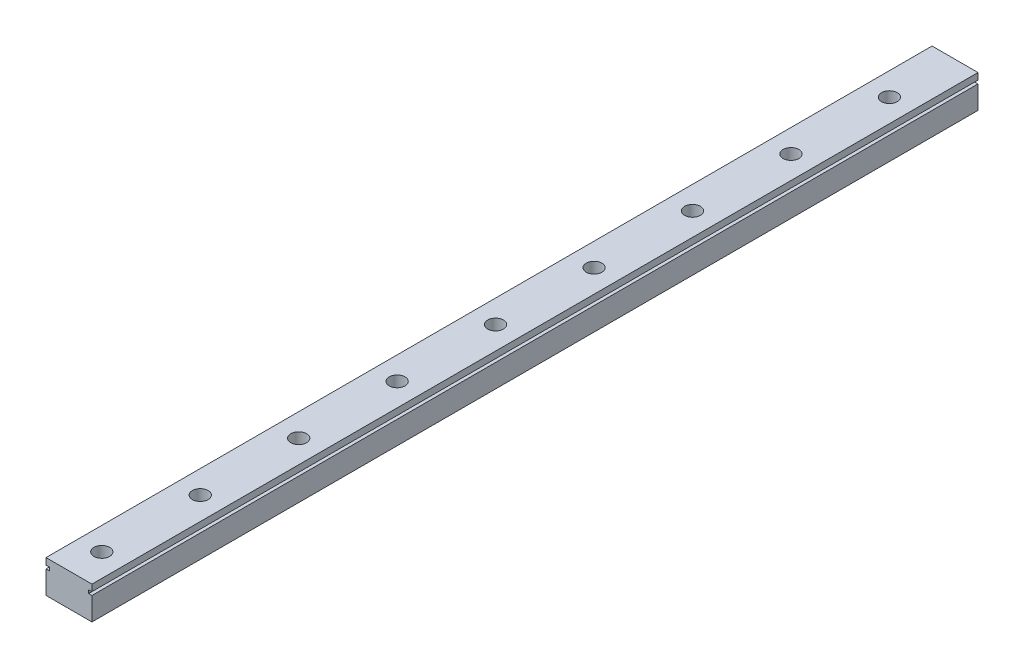
SolidWorks part; units mm, degrees
ref_plane "Front Plane" through (0, 0, 0) normal (0, 0, 1) x (1, 0, 0)
ref_plane "Top Plane" through (0, 0, 0) normal (0, 1, 0) x (1, 0, 0)
ref_plane "Right Plane" through (0, 0, 0) normal (1, 0, 0) x (0, 0, -1)
sketch "Sketch1" plane through (0, 0, 0) normal (0, 0, 1) x (1, 0, 0)
  line L0 (0, 4) -> (0, 5)
  line L1 (0, 0) -> (7, 0)
  line L2 (0, 0) -> (0, 3.5)
  line L3 (0, 5) -> (7, 5)
  line L4 (7, 0) -> (7, 3.5)
  line L5 (0, 4) -> (0.5, 4)
  line L6 (7, 4) -> (7, 5)
  line L7 (0, 3.5) -> (0.5, 3.5)
  line L8 (0.5, 4) -> (0.5, 3.5)
  line L9 (7, 4) -> (6.5, 4)
  line L11 (7, 3.5) -> (6.5, 3.5)
  line L12 (6.5, 4) -> (6.5, 3.5)
  dimension "D1" = 7
  dimension "D2" = 5
  dimension "D3" = 0.5
  dimension "D4" = 1
  dimension "D5" = 0.5
extrude "Boss-Extrude1" add sketch "Sketch1" along normal blind 135
sketch "Sketch2" plane through (0, 5, 0) normal (0, 1, 0) x (1, 0, 0)
  line L0 (3.5, 0) -> (3.5, -135) construction
  line L1 (7, 0) -> (0, 0) construction
  line L2 (7, -135) -> (0, -135) construction
  circle A0 centre (3.5, -130) radius 1.2
  circle A1 centre (3.5, -115) radius 1.2
  circle A2 centre (3.5, -100) radius 1.2
  circle A3 centre (3.5, -85) radius 1.2
  circle A4 centre (3.5, -70) radius 1.2
  circle A5 centre (3.5, -55) radius 1.2
  circle A6 centre (3.5, -40) radius 1.2
  circle A7 centre (3.5, -25) radius 1.2
  circle A8 centre (3.5, -10) radius 1.2
  circle A9 centre (3.5, 5) radius 1.2
  circle A10 centre (3.5, 20) radius 1.2
  circle A11 centre (3.5, 35) radius 1.2
  circle A12 centre (3.5, 50) radius 1.2
  dimension "D1" = 5
  dimension "D3" = 2.4
  dimension "D2" = 13
extrude "Cut-Extrude1" cut sketch "Sketch2" against normal through all
